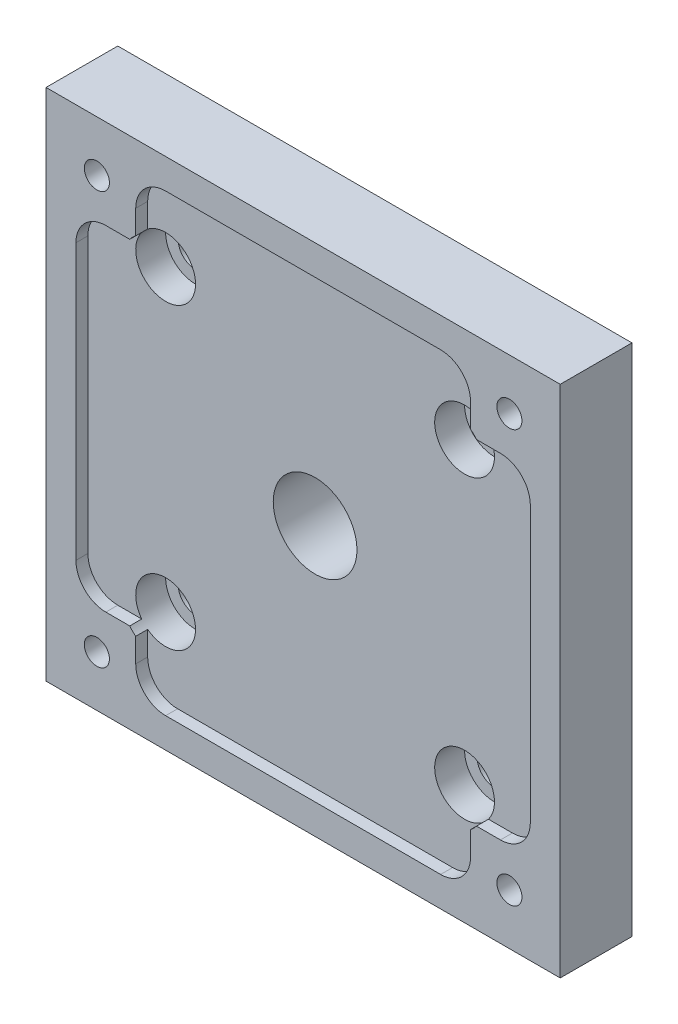
SolidWorks part; units mm, degrees
material "SKD11淬火HRC56-60"
ref_plane "前基準面" through (0, 0, 0) normal (0, 0, 1) x (1, 0, 0)
ref_plane "上基準面" through (0, 0, 0) normal (0, 1, 0) x (1, 0, 0)
ref_plane "右基準面" through (0, 0, 0) normal (1, 0, 0) x (0, 0, -1)
sketch "草图1" plane through (0, 0, 0) normal (0, 0, 1) x (1, 0, 0)
  line L1 (0, 0) -> (86, 0)
  line L2 (0, 0) -> (0, 86)
  line L3 (0, 86) -> (86, 86)
  line L4 (86, 0) -> (86, 86)
  dimension "D1" = 86
extrude "凸台-拉伸1" add sketch "草图1" along normal blind 12
sketch "草图2" plane through (0, 0, 12) normal (0, 0, 1) x (1, 0, 0)
  line L0 (43, 86) -> (43, 0) construction
  line L1 (86, 86) -> (0, 86) construction
  line L2 (0, 0) -> (86, 0) construction
  line L3 (0, 43) -> (86, 43) construction
  line L4 (0, 86) -> (0, 0) construction
  line L5 (86, 0) -> (86, 86) construction
  line L6 (71, 81) -> (15, 81)
  line L7 (15, 81) -> (15, 71)
  line L8 (15, 71) -> (5, 71)
  line L9 (5, 71) -> (5, 15)
  line L10 (81, 71) -> (81, 15)
  line L11 (71, 71) -> (81, 71)
  line L12 (71, 81) -> (71, 71)
  line L13 (71, 5) -> (71, 15)
  line L14 (71, 15) -> (81, 15)
  line L15 (15, 15) -> (5, 15)
  line L16 (15, 5) -> (15, 15)
  line L17 (71, 5) -> (15, 5)
  point P12 (43, 5)
  point P21 (43, 81)
  point P25 (81, 43)
  point P26 (5, 43)
  dimension "D1" = 76
  dimension "D2" = 10
extrude "切除-拉伸1" cut sketch "草图2" against normal blind 2
sketch "草图3" plane through (0, 0, 0) normal (0, 0, -1) x (-1, 0, 0)
  line L0 (-43, 86) -> (-43, 0) construction
  line L1 (-86, 86) -> (0, 86) construction
  line L2 (0, 0) -> (-86, 0) construction
  circle A0 centre (-43, 43) radius 7
  dimension "D1" = 14
extrude "切除-拉伸2" cut sketch "草图3" against normal through all
hole_wizard "M5 螺纹孔1" positions "草图5" profile "草图6" tap size "M5" standard "ISO" end condition through all
sketch "草图5" plane through (0, 0, 12) normal (0, 0, 1) x (1, 0, 0)
  point P0 (77.5, 77.5)
  point P4 (8.5, 77.5)
  point P7 (8.5, 8.5)
  point P10 (77.5, 8.5)
sketch "草图6" plane through (77.5, 77.5, 12) normal (1, 0, 0) x (0, -1, 0)
  line L0 (0, 0) -> (0, 12)
  line L1 (0, 12) -> (2.1, 12)
  line L2 (2.1, 12) -> (2.1, 0)
  line L5 (2.1, 0) -> (0, 0)
  line L11 (0, -6.35) -> (0, 107.95) construction
  dimension "通孔螺纹孔钻头直径" = 4.2
  dimension "通孔螺纹孔钻头深度" = 12
cosmetic thread "孔螺蚊线1" parameters "D2"=5
cosmetic thread "孔螺蚊线2" parameters "D2"=5
cosmetic thread "孔螺蚊线3" parameters "D2"=5
cosmetic thread "孔螺蚊线4" parameters "D2"=5
fillet "圆角1" radius 5 8 edges at (71, 5, 11) (81, 15, 11) (81, 71, 11) (71, 81, 11) (15, 81, 11) (5, 71, 11) (5, 15, 11) (15, 5, 11)
hole_wizard "M5 六角凹头螺钉的柱形沉头孔1" positions "草图8" profile "草图7" counterbore size "M5" standard "ISO" end condition through all
sketch "草图8" plane through (0, 0, 12) normal (0, 0, 1) x (1, 0, 0)
  line L0 (43, 86) -> (43, 0) construction
  line L1 (86, 86) -> (0, 86) construction
  line L2 (0, 0) -> (86, 0) construction
  line L3 (0, 43) -> (86, 43) construction
  line L4 (0, 86) -> (0, 0) construction
  line L5 (86, 0) -> (86, 86) construction
  point P1 (18, 68)
  point P3 (68, 68)
  point P5 (18, 18)
  point P7 (68, 18)
  dimension "D1" = 50
  dimension "D2" = 50
sketch "草图7" plane through (18, 68, 12) normal (1, 0, 0) x (0, -1, 0)
  line L0 (0, 0) -> (0, 12)
  line L1 (0, 12) -> (2.9, 12)
  line L3 (2.9, 12) -> (2.9, 7)
  line L4 (2.9, 7) -> (5, 7)
  line L5 (5, 7) -> (5, 0)
  line L7 (5, 0) -> (0, 0)
  line L11 (0, -6.35) -> (0, 107.95) construction
  dimension "通孔孔直径" = 5.8
  dimension "通孔孔深度" = 12
  dimension "柱形沉头孔直径" = 10
  dimension "柱形沉头孔深度" = 7
